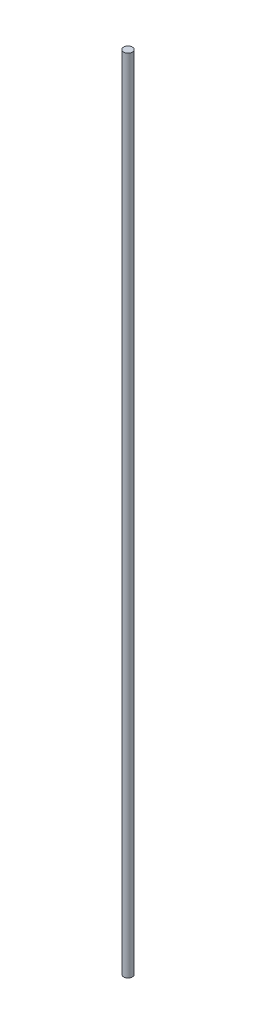
SolidWorks part; units mm, degrees
ref_plane "Front Plane" through (0, 0, 0) normal (0, 0, 1) x (1, 0, 0)
ref_plane "Top Plane" through (0, 0, 0) normal (0, 1, 0) x (1, 0, 0)
ref_plane "Right Plane" through (0, 0, 0) normal (1, 0, 0) x (0, 0, -1)
sketch "Sketch2" plane through (0, 0, 0) normal (0, 1, 0) x (1, 0, 0)
  circle A0 centre (0, 0) radius 4
extrude "Boss-Extrude1" add sketch "Sketch2" along normal blind 730
